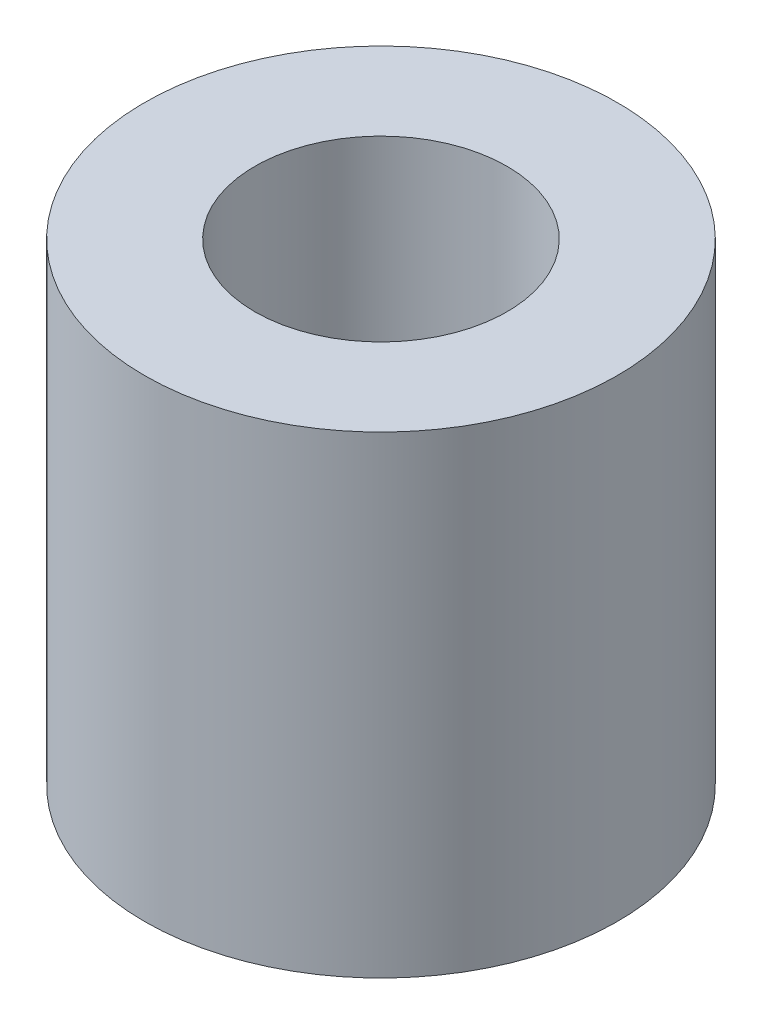
SolidWorks part; units mm, degrees
ref_plane "正面" through (0, 0, 0) normal (0, 0, 1) x (1, 0, 0)
ref_plane "平面" through (0, 0, 0) normal (0, 1, 0) x (1, 0, 0)
ref_plane "右側面" through (0, 0, 0) normal (1, 0, 0) x (0, 0, -1)
sketch "ｽｹｯﾁ1" plane through (0, 0, 0) normal (0, 1, 0) x (1, 0, 0)
  circle A0 centre (0, 0) radius 1.6
  circle A1 centre (0, 0) radius 3
  dimension "D1" = 3.2
  dimension "D2" = 6
extrude "ﾎﾞｽ - 押し出し1" add sketch "ｽｹｯﾁ1" along normal blind 6
